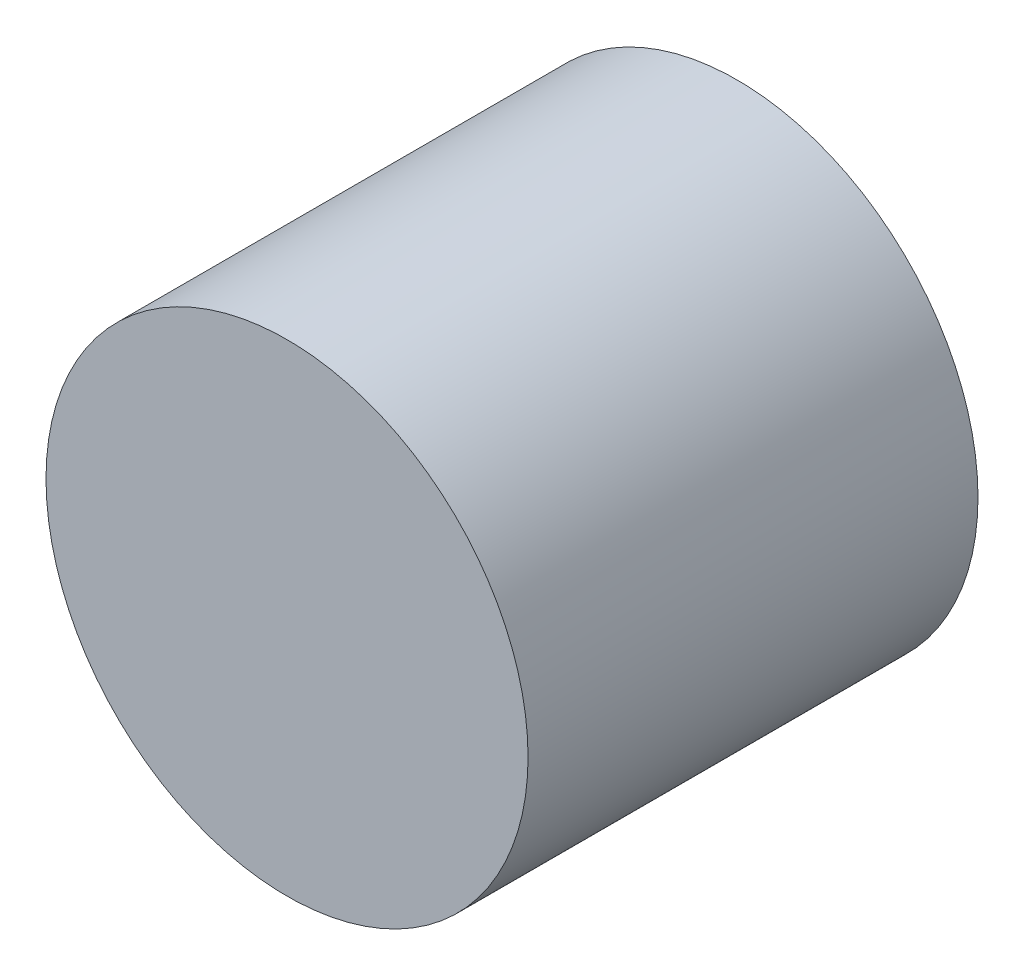
SolidWorks part; units mm, degrees
ref_plane "Front Plane" through (0, 0, 0) normal (0, 0, 1) x (1, 0, 0)
ref_plane "Top Plane" through (0, 0, 0) normal (0, 1, 0) x (1, 0, 0)
ref_plane "Right Plane" through (0, 0, 0) normal (1, 0, 0) x (0, 0, -1)
sketch "Sketch2" plane through (0, 0, 0) normal (0, 0, 1) x (1, 0, 0)
  circle A0 centre (0, 0) radius 7.5
  dimension "D1" = 15
extrude "Boss-Extrude1" add sketch "Sketch2" along normal blind 14
sketch "Sketch3" plane through (0, 0, 0) normal (0, 0, -1) x (-1, 0, 0)
  circle A0 centre (0, 0) radius 3
extrude "Cut-Extrude1" cut sketch "Sketch3" against normal offset from surface (13.8 mm away) 0.2 up to face at (7.5, 0, 14)
